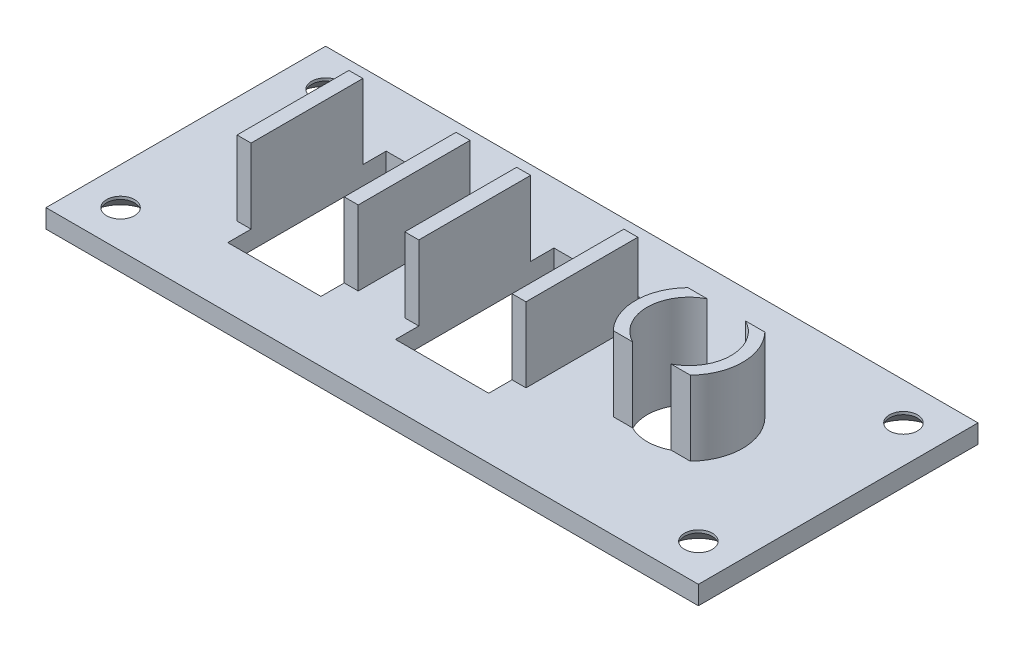
SolidWorks part; units mm, degrees
ref_plane "Front Plane" through (0, 0, 0) normal (0, 0, 1) x (1, 0, 0)
ref_plane "Top Plane" through (0, 0, 0) normal (0, 1, 0) x (1, 0, 0)
ref_plane "Right Plane" through (0, 0, 0) normal (1, 0, 0) x (0, 0, -1)
sketch "Sketch1" plane through (0, 0, 0) normal (0, 1, 0) x (1, 0, 0)
  line L1 (-35, -15) -> (35, -15)
  line L2 (-35, -15) -> (-35, 15)
  line L3 (-35, 15) -> (35, 15)
  line L4 (35, -15) -> (35, 15)
  line L5 (-22, 8.5) -> (-12, 8.5)
  line L6 (-22, 8.5) -> (-22, -8.5)
  line L7 (-22, -8.5) -> (-12, -8.5)
  line L8 (-12, 8.5) -> (-12, -8.5)
  line L9 (-4, 8.5) -> (6, 8.5)
  line L10 (-4, 8.5) -> (-4, -8.5)
  line L11 (-4, -8.5) -> (6, -8.5)
  line L12 (6, 8.5) -> (6, -8.5)
  circle A0 centre (19, 0) radius 4.5
  point P4 (0, 15)
  point P5 (35, 0)
  point P17 (6, 0)
  point P18 (-12, 0)
  dimension "D6" = 9
  dimension "D1" = 30
  dimension "D2" = 70
  dimension "D3" = 10
  dimension "D4" = 17
  dimension "D5" = 8
  dimension "D7" = 13
  dimension "D8" = 13
extrude "Boss-Extrude1" add sketch "Sketch1" along normal blind 2
sketch "Sketch2" plane through (0, 2, 0) normal (0, 1, 0) x (1, 0, 0)
  line L0 (-22, 8.5) -> (-22, -8.5) construction
  line L1 (-23.5, 6) -> (-22, 6)
  line L2 (-23.5, 6) -> (-23.5, -6)
  line L3 (-23.5, -6) -> (-22, -6)
  line L4 (-22, 6) -> (-22, -6)
  line L5 (-12, -8.5) -> (-12, 8.5) construction
  line L6 (-12, 6) -> (-10.5, 6)
  line L7 (-12, 6) -> (-12, -6)
  line L8 (-12, -6) -> (-10.5, -6)
  line L9 (-10.5, 6) -> (-10.5, -6)
  line L10 (-4, 8.5) -> (-4, -8.5) construction
  line L11 (-5.5, 6) -> (-4, 6)
  line L12 (-5.5, 6) -> (-5.5, -6)
  line L13 (-5.5, -6) -> (-4, -6)
  line L14 (-4, 6) -> (-4, -6)
  line L15 (6, -8.5) -> (6, 8.5) construction
  line L16 (6, 6) -> (7.5, 6)
  line L17 (6, 6) -> (6, -6)
  line L18 (6, -6) -> (7.5, -6)
  line L19 (7.5, 6) -> (7.5, -6)
  line L20 (14.8693, 4) -> (16.9384, 4)
  line L21 (14.8693, -4) -> (16.9384, -4)
  line L22 (21.0616, 4) -> (23.1307, 4)
  line L23 (21.0616, -4) -> (23.1307, -4)
  arc A0 (14.8693, 4) -> (14.8693, -4) centre (19, 0) ccw
  circle A1 centre (19, 0) radius 4.5 construction
  circle A2 centre (19, 0) radius 4.5
  arc A3 (23.1307, -4) -> (23.1307, 4) centre (19, 0) ccw
  point P24 (-23.5, 0)
  line M11 (-22, -8.5) -> (-22, 8.5)
  line M13 (-12, 8.5) -> (-12, -8.5)
  line M19 (-4, -8.5) -> (-4, 8.5)
  line M21 (6, 8.5) -> (6, -8.5)
  circle M23 centre (19, 0) radius 4.5
  dimension "D3" = 1.25
  dimension "D1" = 1.5
  dimension "D2" = 12
  dimension "D4" = 8
extrude "Boss-Extrude2" add sketch "Sketch2" along normal blind 8 contours L2 L3 L1 M11 | L9 L6 L8 M13 | L12 L13 L11 M19 | L19 L16 L18 M21 | L20 A0 L21 M23 | L23 A3 L22 M23
sketch "Sketch3" plane through (0, 2, 0) normal (0, 1, 0) x (1, 0, 0)
  line L0 (0, 16.3129) -> (0, -19.5717) construction
  line L1 (-37.0364, 0) -> (35.2209, 0) construction
  line L2 (35, 15) -> (-35, 15) construction
  line L3 (-35, 15) -> (-35, -15) construction
  circle A0 centre (-31, 11) radius 1.5
  circle A1 centre (31, 11) radius 1.5
  circle A2 centre (31, -11) radius 1.5
  circle A3 centre (-31, -11) radius 1.5
  dimension "D1" = 3
  dimension "D2" = 4
  dimension "D3" = 4
extrude "Cut-Extrude1" cut sketch "Sketch3" against normal up to next
chamfer "Chamfer1" distance 1.7 angle 45 4 edges at (-31, 0, -12.5) (31, 0, -12.5) (31, 0, 9.5) (-31, 0, 9.5)
